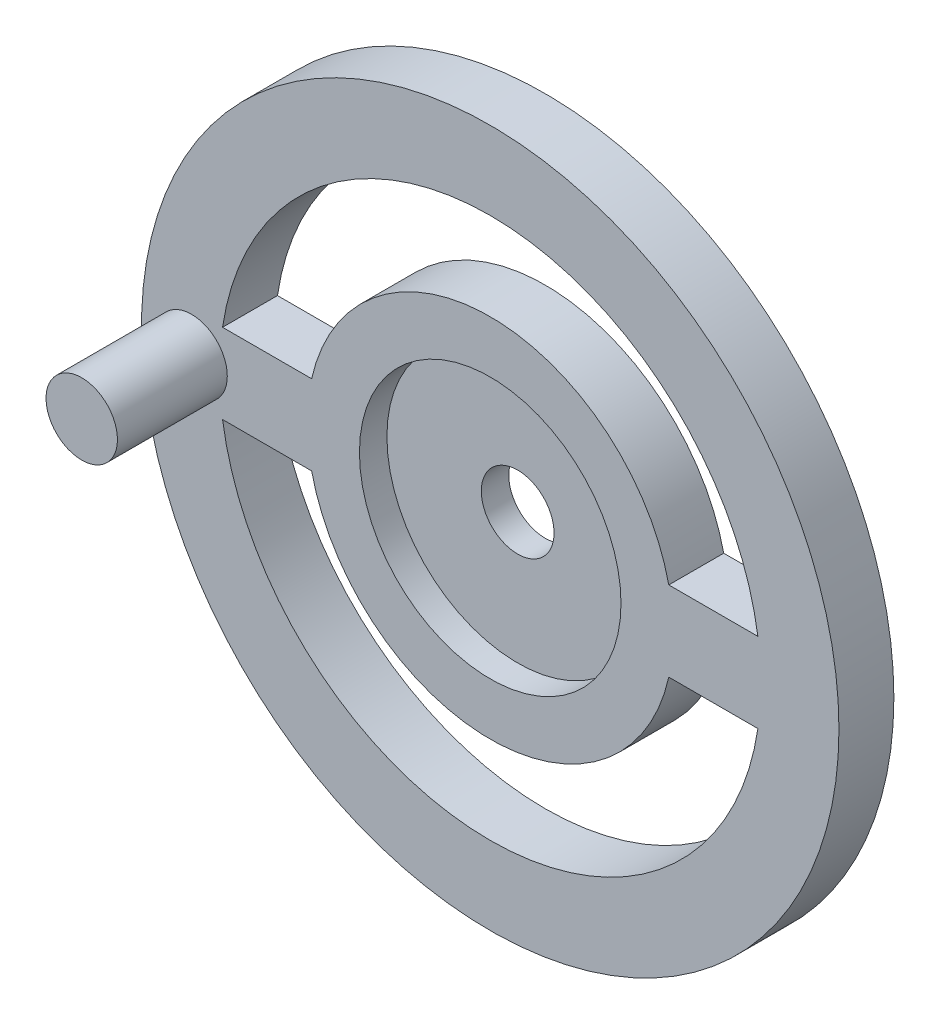
SolidWorks part; units mm, degrees
ref_plane "Front Plane" through (0, 0, 0) normal (0, 0, 1) x (1, 0, 0)
ref_plane "Top Plane" through (0, 0, 0) normal (0, 1, 0) x (1, 0, 0)
ref_plane "Right Plane" through (0, 0, 0) normal (1, 0, 0) x (0, 0, -1)
sketch "Sketch1" plane through (0, 0, 0) normal (0, 0, 1) x (1, 0, 0)
  line L18 (661.6108, -1252.1288) -> (655.1224, -1252.1288)
  line L22 (661.6108, -1257.9447) -> (655.1224, -1257.9447)
  line L24 (694.1108, -1252.1288) -> (687.6224, -1252.1288)
  line L26 (694.1108, -1257.9447) -> (687.6224, -1257.9447)
  circle A1 centre (674.6166, -1255.0367) radius 25.4
  circle A11 centre (674.6166, -1255.0367) radius 2.65
  arc A21 (655.1224, -1257.9447) -> (694.1108, -1257.9447) centre (674.6166, -1255.0367) ccw
  arc A22 (661.6108, -1257.9447) -> (687.6224, -1257.9447) centre (674.6166, -1255.0367) ccw
  arc A23 (687.6224, -1252.1288) -> (661.6108, -1252.1288) centre (674.6166, -1255.0367) ccw
  arc A24 (694.1108, -1252.1288) -> (655.1224, -1252.1288) centre (674.6166, -1255.0367) ccw
  point P0 (661.6108, -1257.9447)
  point P25 (0, 0)
  point P27 (0, 0)
  point P31 (0, 0)
  dimension "D1" = 50.8
extrude "Boss-Extrude1" add sketch "Sketch1" along normal blind 4
sketch "Sketch2" plane through (0, 0, 4) normal (0, 0, 1) x (1, 0, 0)
  line L0 (649.2166, -1255.0367) -> (700.0166, -1255.0367) construction
  circle A0 centre (674.6166, -1255.0367) radius 25.4 construction
  circle A2 centre (652.8667, -1255.0367) radius 2.6
  point P7 (649.752, -1255.0367)
  point P8 (652.8667, -1255.0367)
  dimension "D1" = 5.2
extrude "Boss-Extrude2" add sketch "Sketch2" along normal blind 8
sketch "Sketch3" plane through (0, 0, 0) normal (0, 0, -1) x (-1, 0, 0)
  circle A0 centre (-674.6166, -1255.0367) radius 9.525
  dimension "D1" = 19.05
extrude "Cut-Extrude2" cut sketch "Sketch3" against normal blind 10 from offset 2
